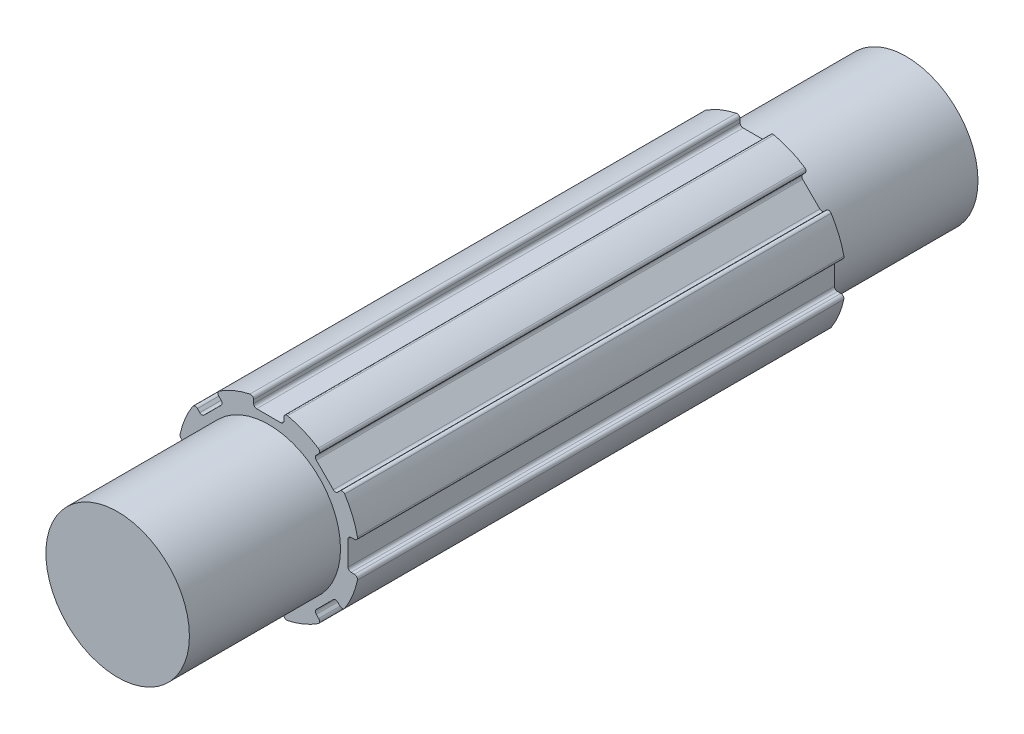
SolidWorks part; units mm, degrees
ref_plane "Front" through (0, 0, 0) normal (0, 0, 1) x (1, 0, 0)
ref_plane "Top" through (0, 0, 0) normal (0, 1, 0) x (1, 0, 0)
ref_plane "Right" through (0, 0, 0) normal (1, 0, 0) x (0, 0, -1)
sketch "Sketch1" plane through (0, 0, 0) normal (0, 0, 1) x (1, 0, 0)
  circle A0 centre (0, 0) radius 6
  dimension "D1" = 12
extrude "Boss-Extrude1" add sketch "Sketch1" along normal mid plane 52.19
sketch "Sketch2" plane through (0, 0, 26.095) normal (0, 0, 1) x (1, 0, 0)
  circle A0 centre (0, 0) radius 4.75
  dimension "D1" = 9.5
extrude "Cut-Extrude1" cut sketch "Sketch2" against normal blind 10 flip side to cut
mirror "Mirror1" about plane through (0, 0, 0) normal (0, 0, 1) of "Cut-Extrude1"
sketch "Sketch3" plane through (0, 0, 0) normal (0, 0, 1) x (1, 0, 0)
  line L5 (-1, 5.25) -> (1, 5.25)
  line L6 (-1, 5.25) -> (-1, 7.25)
  line L7 (-1, 7.25) -> (1, 7.25)
  line L8 (1, 5.25) -> (1, 7.25)
  line L9 (-1, 5.25) -> (1, 7.25) construction
  line L10 (-1, 7.25) -> (1, 5.25) construction
  point P0 (0, 6.25)
  dimension "D1" = 2
  dimension "D2" = 5.25
extrude "Cut-Extrude2" cut sketch "Sketch3" against normal through all both and the other way through all
fillet "Fillet1" radius 0.2 4 edges at (1, 5.25, 0) (1, 5.9161, 0) (-1, 5.25, 0) (-1, 5.9161, 0)
pattern_circular "CirPattern1" count 8 over 360 about axis through (0, 0, 0) along (0, 0, 1) of "Cut-Extrude2", "Fillet1"
